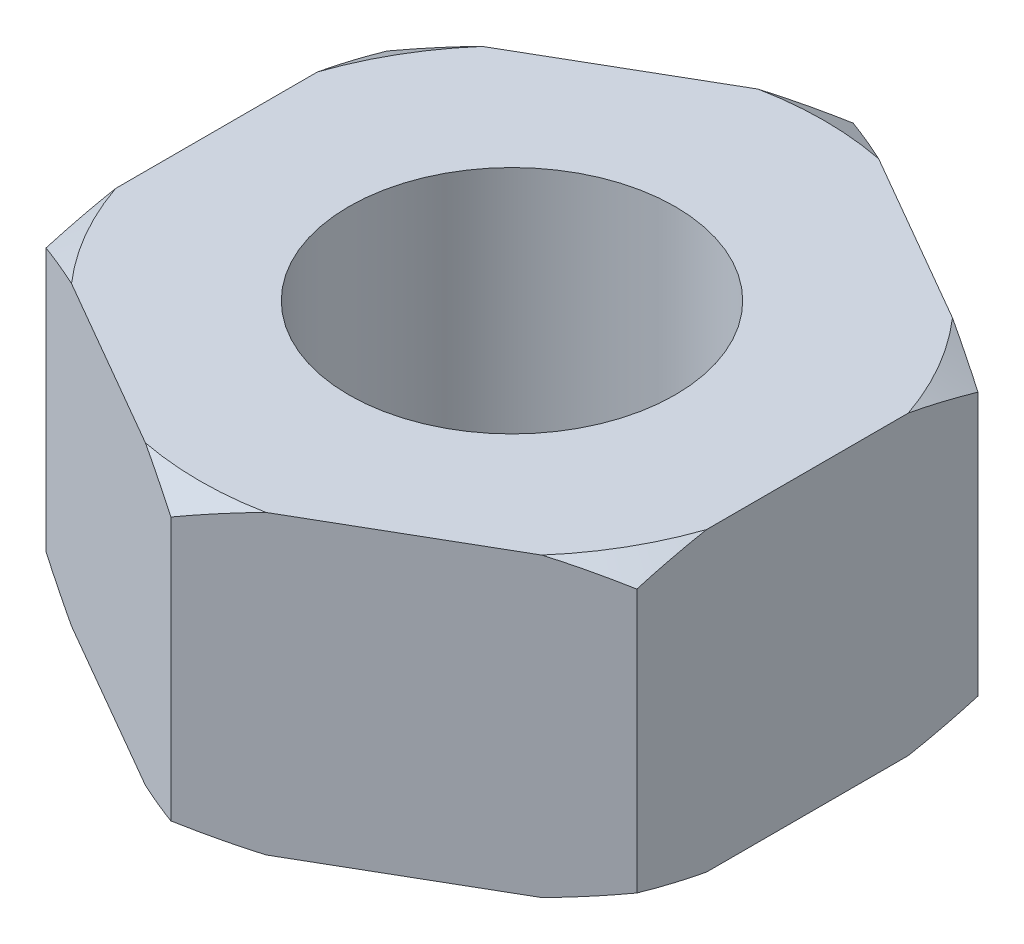
SolidWorks part; units mm, degrees
ref_plane "Спереди" through (0, 0, 0) normal (0, 0, 1) x (1, 0, 0)
ref_plane "Сверху" through (0, 0, 0) normal (0, 1, 0) x (1, 0, 0)
ref_plane "Справа" through (0, 0, 0) normal (1, 0, 0) x (0, 0, -1)
other "Configuration Table"
sketch "Эскиз1" plane through (0, 0, 0) normal (0, 1, 0) x (1, 0, 0)
  circle A0 centre (0, 0) radius 3.85
  dimension "D1" = 7.7
extrude "Бобышка-Вытянуть1" add sketch "Эскиз1" along normal blind 3 contours A0
chamfer "Фаска6" distance 0.4 angle 60 1 edges at (0, 0, 3.85)
chamfer "Фаска7" distance 0.4 angle 60 1 edges at (0, 3, 3.85)
sketch "Эскиз3" plane through (0, 3, 0) normal (0, 1, 0) x (1, 0, 0)
  line L1 (2.9878, -1.725) -> (2.9878, 1.725)
  line L2 (2.9878, 1.725) -> (0, 3.45)
  line L3 (0, 3.45) -> (-2.9878, 1.725)
  line L4 (-2.9878, 1.725) -> (-2.9878, -1.725)
  line L5 (-2.9878, -1.725) -> (0, -3.45)
  line L6 (0, -3.45) -> (2.9878, -1.725)
  circle A0 centre (0, 0) radius 3.45 construction
extrude "Вырез-Вытянуть4" cut sketch "Эскиз3" against normal blind 3 flip side to cut
hole_wizard "Отверстие обработанное метчиком M42" positions "Эскиз6" profile "Эскиз7" tap size "M4" standard "ISO" end condition through all
sketch "Эскиз6" plane through (0, 0, 0) normal (0, -1, 0) x (-1, 0, 0)
  point P0 (0, 0)
sketch "Эскиз7" plane through (0, 0, 0) normal (1, 0, 0) x (0, 0, -1)
  line L0 (0, 0) -> (0, 3)
  line L1 (0, 3) -> (1.65, 3)
  line L2 (1.65, 3) -> (1.65, 0)
  line L5 (1.65, 0) -> (0, 0)
  line L11 (0, -6.35) -> (0, 107.95) construction
  dimension "Диаметр проходного сверла" = 3.3
  dimension "Глубина проходного сверла" = 3
